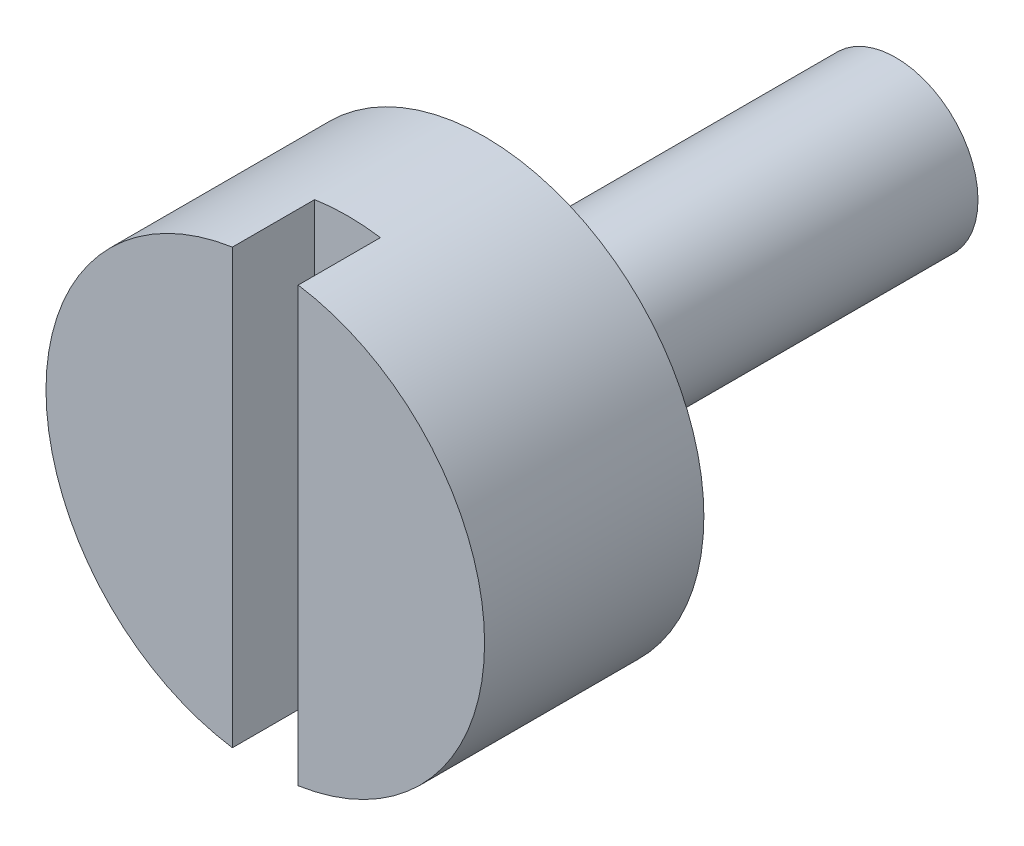
SolidWorks part; units mm, degrees
material "AISI 1020"
ref_plane "Front Plane" through (0, 0, 0) normal (0, 0, 1) x (1, 0, 0)
ref_plane "Top Plane" through (0, 0, 0) normal (0, 1, 0) x (1, 0, 0)
ref_plane "Right Plane" through (0, 0, 0) normal (1, 0, 0) x (0, 0, -1)
sketch "Sketch1" plane through (0, 0, 0) normal (0, 0, 1) x (1, 0, 0)
  circle A0 centre (-20, 0) radius 1.5
extrude "M3_thread_envelope_select_hardware" add sketch "Sketch1" along normal blind 7.5 from offset 40
sketch "Sketch2" plane through (0, 0, 0) normal (0, 0, 1) x (1, 0, 0)
  circle A0 centre (-20, 0) radius 4
extrude "Thumb_head" add sketch "Sketch2" along normal blind 4 from offset 47.5
sketch "Sketch3" plane through (0, 0, 0) normal (0, 0, 1) x (1, 0, 0)
  line L0 (-20.6, -5) -> (-19.4, -5)
  line L1 (-19.4, -5) -> (-19.4, 5)
  line L2 (-19.4, 5) -> (-20.6, 5)
  line L3 (-20.6, 5) -> (-20.6, -5)
extrude "Driver_slot" cut sketch "Sketch3" along normal blind 3 from offset 50
